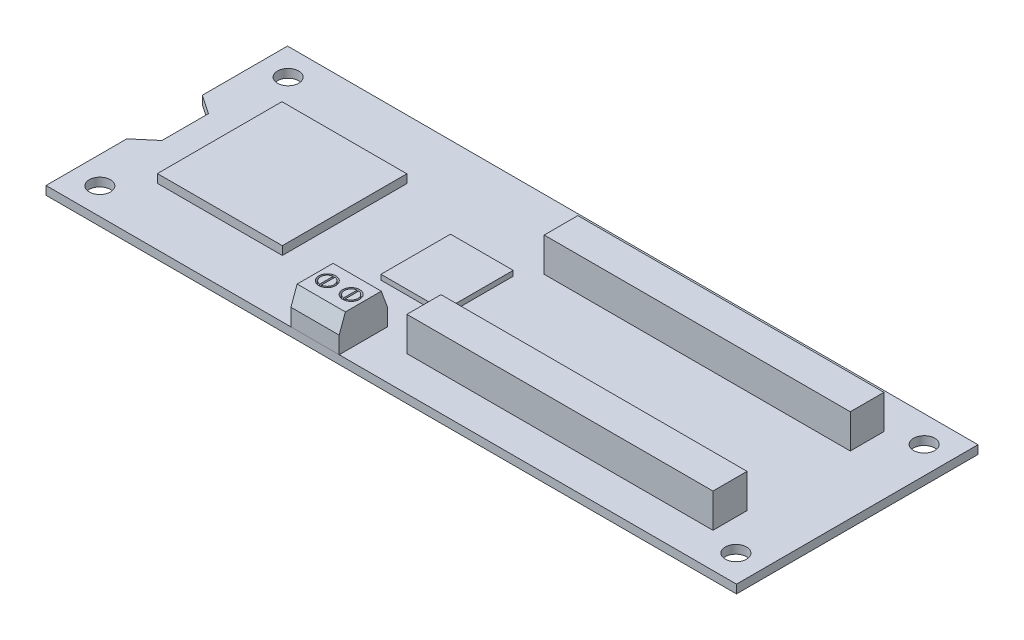
SolidWorks part; units mm, degrees
ref_plane "Front Plane" through (0, 0, 0) normal (0, 0, 1) x (1, 0, 0)
ref_plane "Top Plane" through (0, 0, 0) normal (0, 1, 0) x (1, 0, 0)
ref_plane "Right Plane" through (0, 0, 0) normal (1, 0, 0) x (0, 0, -1)
sketch "Sketch1" plane through (0, 0, 0) normal (0, 1, 0) x (1, 0, 0)
  line L1 (-51.562, -18.034) -> (51.562, -18.034)
  line L2 (-51.562, -18.034) -> (-51.562, 18.034)
  line L3 (-51.562, 18.034) -> (51.562, 18.034)
  line L4 (51.562, -18.034) -> (51.562, 18.034)
  line L5 (-51.562, -18.034) -> (51.562, 18.034) construction
  line L6 (-51.562, 18.034) -> (51.562, -18.034) construction
  line L7 (-47.498, 14.0589) -> (47.498, 14.0589) construction
  line L8 (-47.498, 14.0589) -> (-47.498, -14.0589) construction
  line L9 (-47.498, -14.0589) -> (47.498, -14.0589) construction
  line L10 (47.498, 14.0589) -> (47.498, -14.0589) construction
  line L11 (-47.498, 14.0589) -> (47.498, -14.0589) construction
  line L12 (-47.498, -14.0589) -> (47.498, 14.0589) construction
  circle A0 centre (-47.498, 14.0589) radius 1.5875
  circle A1 centre (-47.498, -14.0589) radius 1.5875
  circle A2 centre (47.498, 14.0589) radius 1.5875
  circle A3 centre (47.498, -14.0589) radius 1.5875
  point P0 (0, 0)
  point P6 (0, 0)
  dimension "D3" = 28.1178
  dimension "D5" = 3.175
  dimension "D1" = 36.068
  dimension "D2" = 103.124
  dimension "D4" = 94.996
extrude "Boss-Extrude2" add sketch "Sketch1" along normal blind 1.27
sketch "Sketch2" plane through (0, 1.27, 0) normal (0, 1, 0) x (1, 0, 0)
  line L0 (-51.562, 5.3215) -> (-48.7226, 3.389)
  line L1 (-51.562, 18.034) -> (-51.562, -18.034) construction
  line L2 (-48.7226, 3.389) -> (-48.7226, -3.5575)
  line L3 (-48.7226, -3.5575) -> (-51.562, -5.96)
  line L4 (-51.562, -5.96) -> (-51.562, 5.3215)
extrude "Cut-Extrude1" cut sketch "Sketch2" against normal through all
sketch "Sketch3" plane through (0, 1.27, 0) normal (0, 1, 0) x (1, 0, 0)
  line L1 (-43.5126, 9.1527) -> (-24.8597, 9.1527)
  line L2 (-43.5126, 9.1527) -> (-43.5126, -9.4409)
  line L3 (-43.5126, -9.4409) -> (-24.8597, -9.4409)
  line L4 (-24.8597, 9.1527) -> (-24.8597, -9.4409)
  point P4 (0, 0)
  point P5 (0, 0)
  point P6 (0, 0)
  point P7 (0, 0)
  point P8 (-43.5126, 9.1527)
  point P9 (-24.8597, -9.4409)
extrude "Boss-Extrude3" add sketch "Sketch3" along normal blind 1.27
sketch "Sketch4" plane through (0, 1.27, 0) normal (0, 1, 0) x (1, 0, 0)
  line L1 (-14.3016, 5.1146) -> (-4.933, 5.1146)
  line L2 (-14.3016, 5.1146) -> (-14.3016, -5.2654)
  line L3 (-14.3016, -5.2654) -> (-4.933, -5.2654)
  line L4 (-4.933, 5.1146) -> (-4.933, -5.2654)
  point P4 (-14.3016, 5.1146)
  point P5 (-4.933, -5.2654)
extrude "Boss-Extrude4" add sketch "Sketch4" along normal blind 0.762
sketch "Sketch5" plane through (0, 1.27, 0) normal (0, 1, 0) x (1, 0, 0)
  line L0 (51.562, 0) -> (-48.7226, -0.0842) construction
  line L1 (51.562, -18.034) -> (51.562, 18.034) construction
  line L2 (-48.7226, -3.5575) -> (-48.7226, 3.389) construction
  line L4 (-2.8699, 12.705) -> (42.842, 12.705)
  line L5 (-2.8699, 12.705) -> (-2.8699, 7.68)
  line L6 (-2.8699, 7.68) -> (42.842, 7.68)
  line L7 (42.842, 12.705) -> (42.842, 7.68)
  line L8 (-2.8699, -7.7364) -> (42.842, -7.7364)
  line L9 (-2.8699, -7.7364) -> (-2.8699, -12.8296)
  line L10 (-2.8699, -12.8296) -> (42.842, -12.8296)
  line L11 (42.842, -7.7364) -> (42.842, -12.8296)
extrude "Boss-Extrude6" add sketch "Sketch5" along normal blind 5.08
sketch "Sketch6" plane through (0, 1.27, 0) normal (0, 1, 0) x (1, 0, 0)
  line L0 (-51.562, -18.034) -> (51.562, -18.034) construction
  line L1 (-14.9805, -10.8213) -> (-7.7761, -10.8213)
  line L2 (-14.9805, -10.8213) -> (-14.9805, -18.034)
  line L3 (-14.9805, -18.034) -> (-7.7761, -18.034)
  line L4 (-7.7761, -10.8213) -> (-7.7761, -18.034)
extrude "Boss-Extrude8" add sketch "Sketch6" along normal blind 5.08 separate body
chamfer "Chamfer1" distance 2.54 angle 20 2 edges at (-11.3783, 6.35, 10.8213) (-11.3783, 6.35, 18.034)
sketch "Sketch7" plane through (0, 6.35, 0) normal (0, 1, 0) x (1, 0, 0)
  line L0 (-11.3783, -11.7458) -> (-11.3783, -17.1095) construction
  line L1 (-7.7761, -11.7458) -> (-14.9805, -11.7458) construction
  line L2 (-14.9805, -17.1095) -> (-7.7761, -17.1095) construction
  line L3 (-14.9805, -14.4276) -> (-7.7761, -14.4276) construction
  line L4 (-14.9805, -11.7458) -> (-14.9805, -17.1095) construction
  line L5 (-7.7761, -17.1095) -> (-7.7761, -11.7458) construction
  line L6 (-13.1596, -14.4276) -> (-9.5969, -14.4276) construction
  circle A0 centre (-13.1596, -14.4276) radius 1.27
  circle A1 centre (-9.5969, -14.4276) radius 1.27
  point P17 (-11.3783, -14.4276)
  dimension "D1" = 2.54
extrude "Cut-Extrude2" cut sketch "Sketch7" against normal blind 0.762
sketch "Sketch8" plane through (0, 5.588, 0) normal (0, 1, 0) x (1, 0, 0)
  line L0 (-13.2866, -14.4276) -> (-13.0326, -14.4276) construction
  line L1 (-9.7239, -14.4276) -> (-9.4699, -14.4276) construction
  line L2 (-13.2866, -13.4196) -> (-13.2866, -15.4357)
  line L3 (-13.0326, -15.4357) -> (-13.0326, -13.4196)
  line L4 (-9.7239, -15.4357) -> (-9.7239, -13.4196)
  line L5 (-9.4699, -15.4357) -> (-9.4699, -13.4196)
  circle A0 centre (-13.1596, -14.4276) radius 1.016
  circle A1 centre (-9.5969, -14.4276) radius 1.016
  point P9 (-13.1596, -14.4276)
  point P12 (-9.5969, -14.4276)
  point P14 (-13.2866, -14.4276)
  point P15 (0, 0)
  point P18 (-13.0326, -14.4276)
  point P21 (-9.7239, -14.4276)
  point P24 (-9.4699, -14.4276)
  dimension "D1" = 2.032
  dimension "D2" = 0.254
extrude "Boss-Extrude10" add sketch "Sketch8" along normal blind 0.762 separate body contours L2 A0 | L3 A0 | L4 A1 | L5 A1
